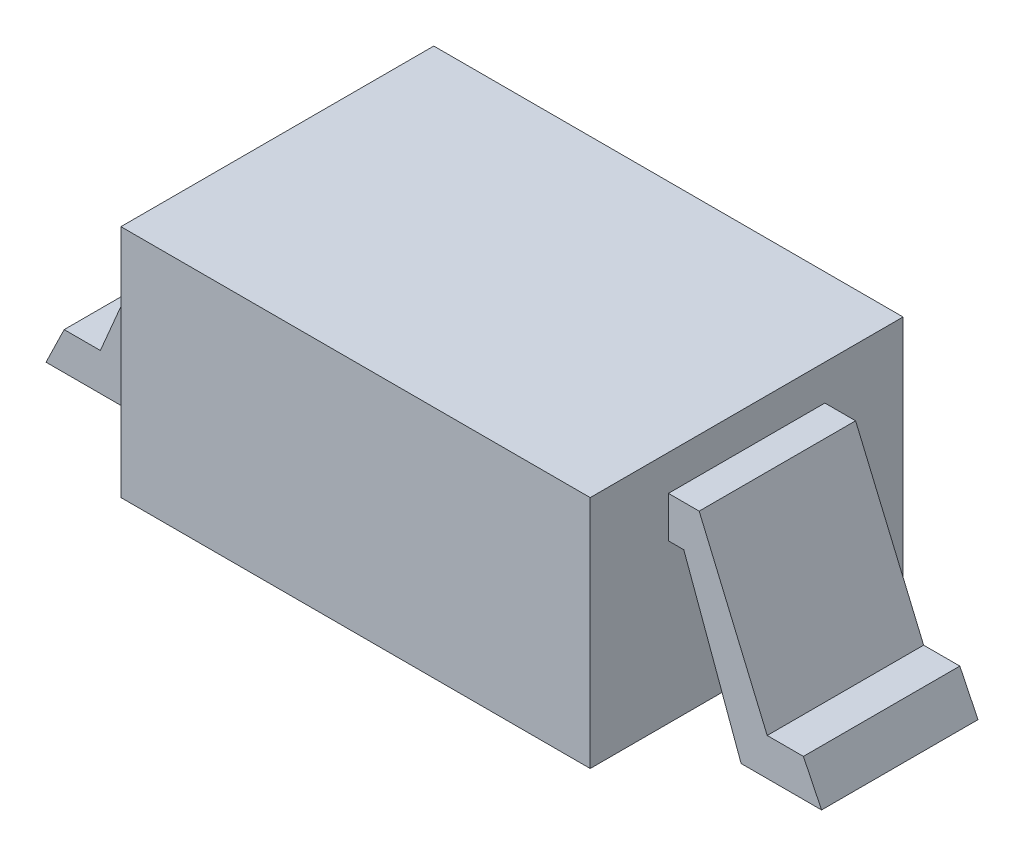
SolidWorks part; units mm, degrees
ref_plane "前视基准面" through (0, 0, 0) normal (0, 0, 1) x (1, 0, 0)
ref_plane "上视基准面" through (0, 0, 0) normal (0, 1, 0) x (1, 0, 0)
ref_plane "右视基准面" through (0, 0, 0) normal (1, 0, 0) x (0, 0, -1)
sketch "草图1" plane through (0, 0, 0) normal (0, 0, 1) x (1, 0, 0)
  line L1 (0, 0) -> (6, 0)
  line L2 (0, 0) -> (0, -3)
  line L3 (0, -3) -> (6, -3)
  line L4 (6, 0) -> (6, -3)
  dimension "D1" = 6
  dimension "D2" = 3
extrude "凸台-拉伸1" add sketch "草图1" along normal blind 4
ref_plane "基准面1" through (0, 0, 2) normal (0, 0, 1) x (1, 0, 0)
sketch "草图2" plane through (0, 0, 2) normal (0, 0, 1) x (1, 0, 0)
  line L0 (0, 0.9906) -> (0, -4.0834) construction
  line L1 (0, -0.4532) -> (-0.393, -0.4532)
  line L2 (-0.393, -0.4532) -> (-1.2629, -2.5026)
  line L3 (-1.2629, -2.9799) -> (-0.9293, -2.9799)
  line L4 (-0.9293, -2.9799) -> (-0.1965, -0.9792)
  line L5 (-0.1965, -0.9792) -> (0, -0.9792)
  line L6 (0, -0.4532) -> (0, -0.9792)
  line L7 (-1.2629, -2.5026) -> (-1.7256, -2.5026)
  line L8 (7.7256, -2.5026) -> (7.958, -2.9799)
  line L9 (-1.958, -2.9799) -> (-1.2629, -2.9799)
  line L10 (3, 1.9904) -> (3, -5.2358) construction
  line L11 (7.958, -2.9799) -> (7.2629, -2.9799)
  line L12 (7.2629, -2.5026) -> (7.7256, -2.5026)
  line L13 (6, -0.4532) -> (6, -0.9792)
  line L14 (6.1965, -0.9792) -> (6, -0.9792)
  line L15 (6.9293, -2.9799) -> (6.1965, -0.9792)
  line L16 (7.2629, -2.9799) -> (6.9293, -2.9799)
  line L17 (6.393, -0.4532) -> (7.2629, -2.5026)
  line L18 (6, -0.4532) -> (6.393, -0.4532)
  line L20 (-1.7256, -2.5026) -> (-1.958, -2.9799)
extrude "凸台-拉伸2" add sketch "草图2" along normal mid plane 2
